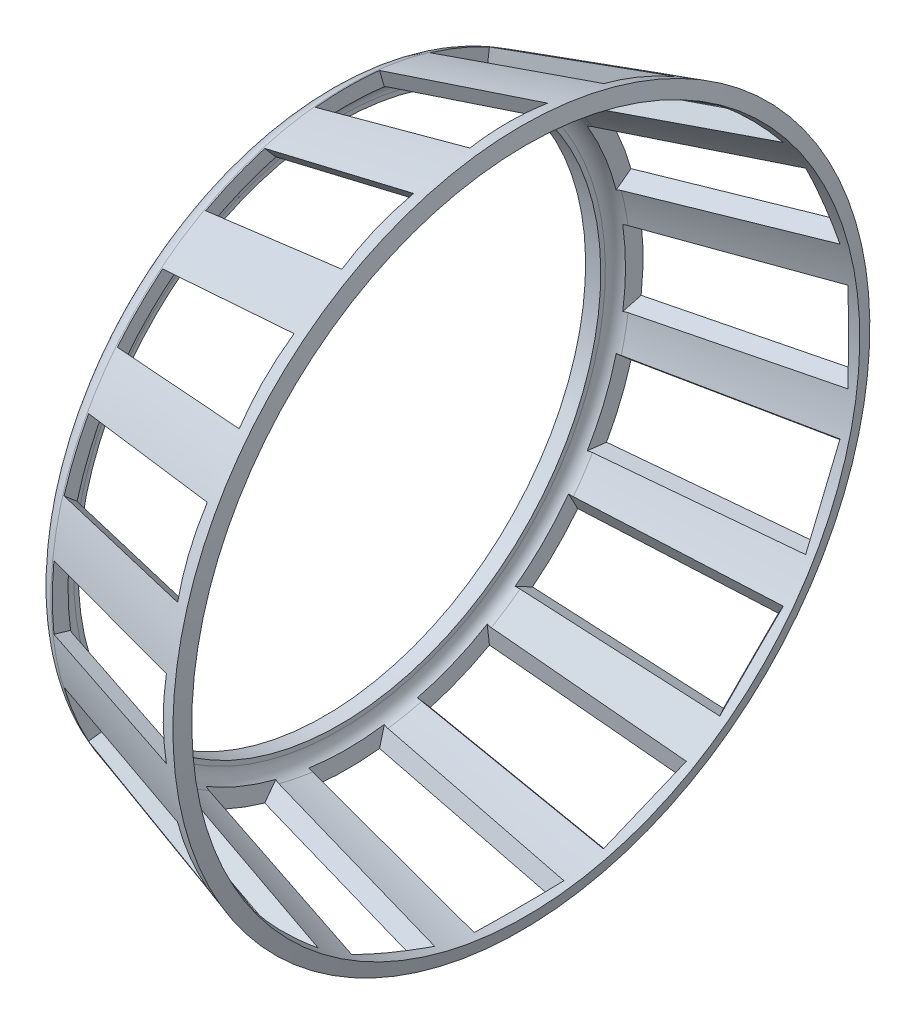
SolidWorks part; units mm, degrees
ref_plane "Plan1" through (0, 0, 0) normal (0, 0, 1) x (1, 0, 0)
ref_plane "Plan2" through (0, 0, 0) normal (0, 1, 0) x (1, 0, 0)
ref_plane "Plan3" through (0, 0, 0) normal (1, 0, 0) x (0, 0, -1)
sketch "Esquisse1" plane through (0, 0, 0) normal (0, 0, 1) x (1, 0, 0)
  line L0 (-14.7804, 19.4666) -> (-3.19, 23.0101)
  line L1 (-16.1957, 17.5539) -> (-16.1957, 17.2482)
  line L2 (-3.19, 23.0101) -> (-2.8976, 22.0538)
  line L3 (-2.8976, 22.0538) -> (-14.4881, 18.5103)
  line L4 (-15.1957, 17.5539) -> (-15.1957, 17.2482)
  line L5 (-15.1957, 17.2482) -> (-16.1957, 17.2482)
  line L6 (-3.3856, 0) -> (-14, 0) construction
  line L7 (-3.3856, 19.25) -> (-3.3856, -19.25) construction
  line L8 (-14, 16.4059) -> (-14, -16.4059) construction
  line L9 (-8.6928, 0) -> (-8.6928, 23.7971) construction
  line L10 (-30.5639, 12.7378) -> (3.0961, 22.0886) construction
  line L11 (5.1368, 22.6555) -> (-76.4156, 0) construction
  arc A0 (-15.1957, 17.5539) -> (-14.4881, 18.5103) centre (-14.1957, 17.5539) cw
  arc A1 (-16.1957, 17.5539) -> (-14.7804, 19.4666) centre (-14.1957, 17.5539) cw
  point P13 (-16.1957, 19.0339)
  point P14 (-8.6928, 20.282)
  point P19 (-8.6928, 0)
  dimension "D4" = 1
  dimension "D7" = 2
  dimension "D1" = 1
  dimension "D2" = 17
  dimension "D3" = 1
  dimension "D5" = 1
  dimension "D6" = 0.5
  dimension "D8" = 13.6
revolve "Base-Révolution" add sketch "Esquisse1" angle 360 about L6
sketch "Esquisse3" plane through (0, 0, 0) normal (0, 0, 1) x (1, 0, 0)
  line L0 (-3.19, 23.0101) -> (-10.971, 20.6312) construction
  line L1 (-3.19, 23.0101) -> (-3.19, -23.0101) construction
  line L2 (-3.19, 23.0101) -> (-14.7804, 19.4666) construction
ref_plane "Plan4" through (-8.9852, 21.2383, 0) normal (-0.2924, 0.9563, 0) x (0, 0, -1)
sketch "Esquisse4" plane through (-8.9852, 21.2383, 0) normal (-0.2924, 0.9563, 0) x (0, 0, -1)
  line L0 (0, 9.5066) -> (0, -9.0797) construction
  line L1 (0, 0.8546) -> (0, 11.0052) construction
  line L3 (2.0736, 5.9356) -> (2.5122, -5.098)
  line L4 (-2.0736, 5.9356) -> (-2.5122, -5.098)
  line L5 (-2.0736, 5.9356) -> (2.0736, 5.9356)
  line L6 (2.5122, -5.098) -> (-2.5122, -5.098)
  line L7 (2.5936, 5.4438) -> (3.2191, -10.2925) construction
  line L8 (-4.5399, -4.598) -> (5.2637, -4.598) construction
  line L9 (-4.0136, 5.4356) -> (3.0924, 5.4356) construction
  line L10 (2.9897, -4.521) -> (2.5913, 5.5023) construction
  ellipse E0 centre (0, -4.5211) end of major axis (2.9897, -4.5211) minor radius 0.0769 construction
  ellipse E1 centre (0, 5.5023) end of major axis (-2.5913, 5.5023) minor radius 0.0667 construction
  point P9 (0, -5.098)
  point P12 (0, 5.9356)
  dimension "D1" = 0.5
  dimension "D2" = 0.5
  dimension "D3" = 0.5
extrude "Enlèv. mat.-Extru.1" cut sketch "Esquisse4" against normal blind 2 draft 20
pattern_circular "Répétition circulaire1" count 16 over 360 about axis through (-3.3856, 0, 0) along (-1, 0, 0)
